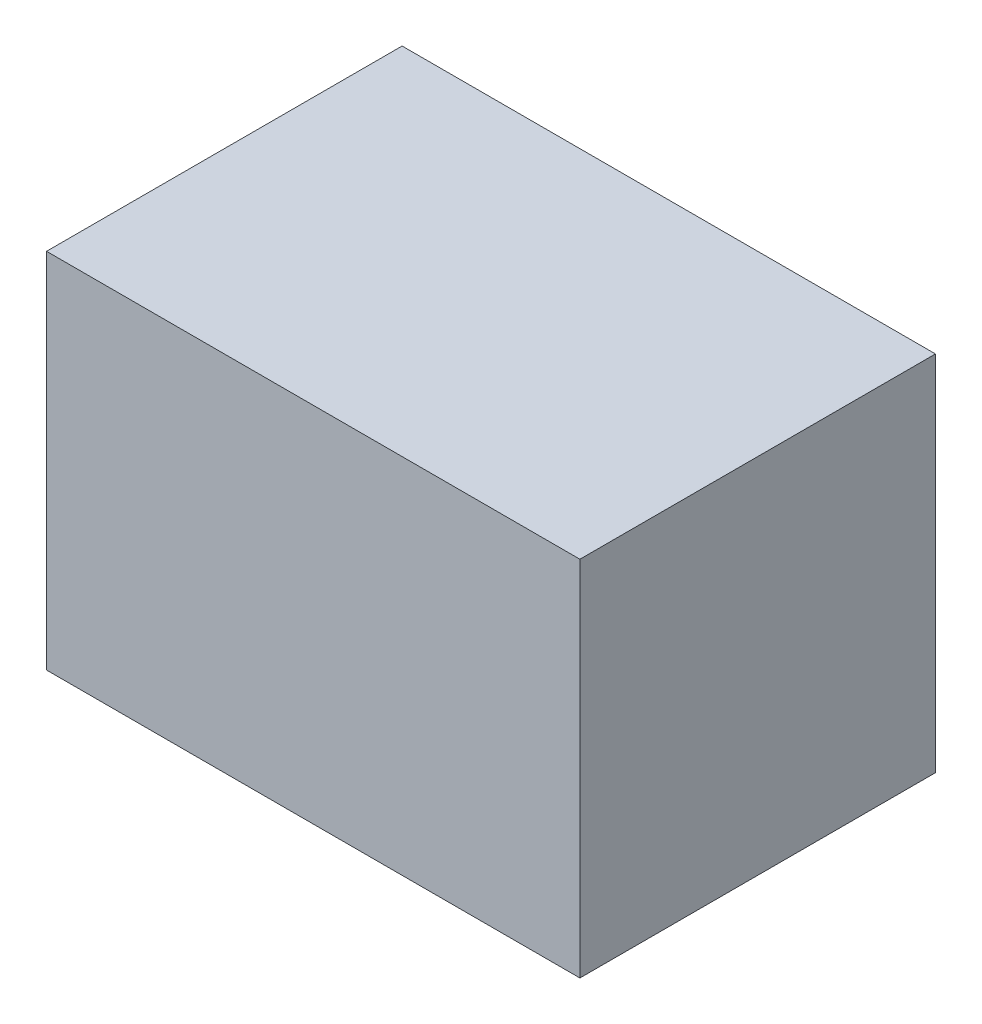
SolidWorks part; units mm, degrees
material "PET"
ref_plane "Front Plane" through (0, 0, 0) normal (0, 0, 1) x (1, 0, 0)
ref_plane "Top Plane" through (0, 0, 0) normal (0, 1, 0) x (1, 0, 0)
ref_plane "Right Plane" through (0, 0, 0) normal (1, 0, 0) x (0, 0, -1)
sketch "Sketch1" plane through (0, 0, 0) normal (0, 1, 0) x (1, 0, 0)
  line L1 (-75, -50) -> (75, -50)
  line L2 (-75, -50) -> (-75, 50)
  line L3 (-75, 50) -> (75, 50)
  line L4 (75, -50) -> (75, 50)
  line L5 (-75, -50) -> (75, 50) construction
  line L6 (-75, 50) -> (75, -50) construction
  point P0 (0, 0)
  dimension "D1" = 100
  dimension "D2" = 150
extrude "Boss-Extrude1" add sketch "Sketch1" along normal blind 100
shell "Shell1" thickness 2
sketch "Sketch3" plane through (0, 2, 0) normal (0, 1, 0) x (1, 0, 0)
  line L0 (-73, 0) -> (0, 0)
  line L1 (-54.75, 48) -> (-54.75, -48)
  line L2 (73, 48) -> (-73, 48) construction
  line L3 (-73, -48) -> (73, -48) construction
  line L4 (-36.5, 48) -> (-36.5, -48)
  line L5 (73, 48) -> (-73, 48) construction
  line L6 (-73, -48) -> (73, -48) construction
  line L7 (0, 48) -> (0, -48)
  line L9 (73, -48) -> (73, 48) construction
  line L10 (-73, 48) -> (-73, -48) construction
  line L11 (-18.25, 48) -> (-18.25, -48)
  line L12 (36.5, 48) -> (36.5, -48)
  dimension "D1" = 18.25
  dimension "D2" = 18.25
  dimension "D3" = 18.25
  dimension "D4" = 36.5
extrude "Extrude-Thin1" add sketch "Sketch3" along normal through all thin
sketch "Sketch4" plane through (0, 0, 48) normal (0, 0, -1) x (-1, 0, 0)
  line L0 (0, 2) -> (-34.5, 2) construction
  line L1 (-36.5, 2) -> (-73, 2) construction
  line L2 (-34.5, 100) -> (-34.5, 2) construction
  line L3 (-73, 100) -> (-73, 2) construction
  circle A0 centre (-17, 67) radius 15
  circle A1 centre (-55.5, 67) radius 15
  circle A2 centre (-17, 22) radius 15
  circle A3 centre (-55.5, 22) radius 15
  circle A4 centre (-55.5, 67) radius 13.5
  circle A5 centre (-17, 67) radius 13.5
  circle A6 centre (-55.5, 22) radius 13.5
  circle A7 centre (-17, 22) radius 13.5
  dimension "D1" = 30
  dimension "D2" = 20
  dimension "D3" = 45
  dimension "D4" = 20
  dimension "D5" = 45
  dimension "D6" = 17.5
  dimension "D7" = 17.5
  dimension "D8" = 17.5
  dimension "D9" = 17.5
  dimension "D10" = 27
  dimension "D11" = 27
  dimension "D12" = 27
  dimension "D13" = 27
extrude "Boss-Extrude2" add sketch "Sketch4" along normal blind 75
ref_plane "Plane1" through (0, 0, -35) normal (0, 0, 1) x (1, 0, 0)
sketch "Sketch6" plane through (0, 0, -35) normal (0, 0, 1) x (1, 0, 0)
  circle A0 centre (17, 67) radius 6.25
  circle A1 centre (17, 67) radius 15 construction
  dimension "D1" = 12.5
loft "Loft2" add profiles "Sketch6" section "Sketch6" section edge at (2, 67, -27)
sketch "Sketch7" plane through (0, 0, -35) normal (0, 0, 1) x (1, 0, 0)
  circle A0 centre (55.5, 67) radius 6.25
  circle A1 centre (55.5, 67) radius 15 construction
  dimension "D1" = 12.5
loft "Loft3" add profiles "Sketch7" section edge at (40.5, 67, -27) section "Sketch7"
sketch "Sketch11" plane through (0, 0, -35) normal (0, 0, -1) x (-1, 0, 0)
  circle A0 centre (-17, 67) radius 6.25
  circle A1 centre (-17, 67) radius 6.25 construction
  circle A2 centre (-17, 67) radius 5
  dimension "D1" = 10
extrude "Boss-Extrude3" add sketch "Sketch11" along normal blind 5
sketch "Sketch12" plane through (0, 0, -35) normal (0, 0, -1) x (-1, 0, 0)
  circle A0 centre (-55.5, 67) radius 6.25
  circle A1 centre (-55.5, 67) radius 5
  circle A8 centre (-55.5, 67) radius 6.25 construction
  dimension "D1" = 10
extrude "Boss-Extrude4" add sketch "Sketch12" along normal blind 5 contours A0
sketch "Sketch13" plane through (0, 100, 0) normal (0, 1, 0) x (1, 0, 0)
  line L1 (-75, 50) -> (75, 50)
  line L2 (-75, 50) -> (-75, -50)
  line L3 (-75, -50) -> (75, -50)
  line L4 (75, 50) -> (75, -50)
extrude "Boss-Extrude5" add sketch "Sketch13" along normal blind 2
